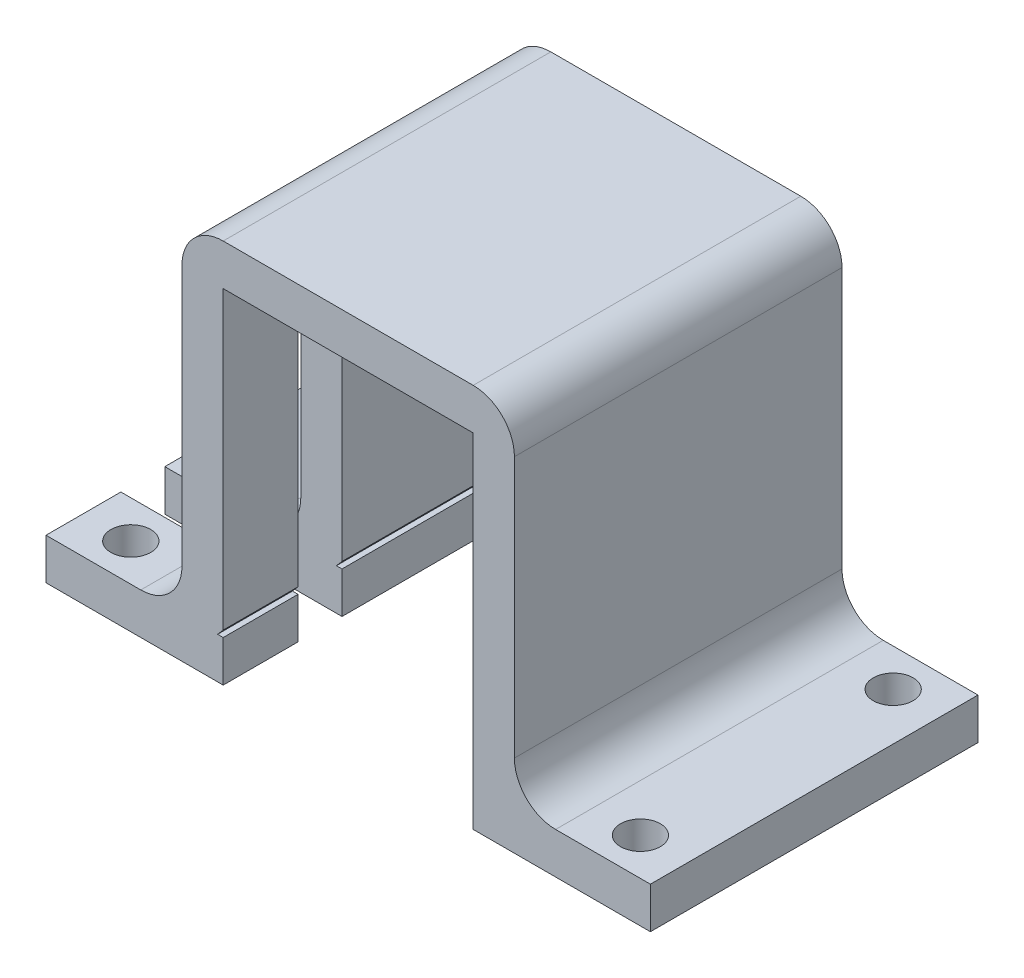
SolidWorks part; units mm, degrees
ref_plane "Front Plane" through (0, 0, 0) normal (0, 0, 1) x (1, 0, 0)
ref_plane "Top Plane" through (0, 0, 0) normal (0, 1, 0) x (1, 0, 0)
ref_plane "Right Plane" through (0, 0, 0) normal (1, 0, 0) x (0, 0, -1)
sketch "Sketch1" plane through (0, 0, 0) normal (0, 0, 1) x (1, 0, 0)
  line L1 (-9.1, 11) -> (9.1, 11)
  line L2 (-9.1, 11) -> (-9.1, -11)
  line L4 (9.1, 11) -> (9.1, -11)
  line L7 (-9.1, 14) -> (9.1, 14)
  line L8 (-12.1, 11) -> (-12.1, -8)
  line L9 (-12.1, -14) -> (-9.1, -14)
  line L10 (12.1, 11) -> (12.1, -8)
  line L12 (-9.1, -11) -> (-9.1, -14)
  line L13 (-22, -11) -> (-15.1, -11)
  line L14 (-22, -11) -> (-22, -14)
  line L15 (-22, -14) -> (-9.1, -14)
  line L16 (22, -11) -> (22, -14)
  line L17 (9.1, -11) -> (9.1, -14)
  line L18 (9.1, -14) -> (12.1, -14)
  line L19 (-9.5071, -11) -> (-9.1, -11)
  line L20 (-9.5071, -11) -> (-9.1, -10.5289) construction
  line L21 (15.1, -11) -> (22, -11)
  line L22 (9.1, -14) -> (22, -14)
  arc A0 (-9.1, 14) -> (-12.1, 11) centre (-9.1, 11) ccw
  arc A1 (9.1, 14) -> (12.1, 11) centre (9.1, 11) cw
  arc A2 (-12.1, -8) -> (-15.1, -11) centre (-15.1, -8) cw
  arc A3 (12.1, -8) -> (15.1, -11) centre (15.1, -8) ccw
  point P0 (0, 0)
  point P6 (0, 0)
  point P8 (12.1, -8)
  point P10 (0, 0)
  point P17 (0, -12.5)
  point P23 (0, 0)
  dimension "D5" = 3
  dimension "D9" = 3
  dimension "D1" = 22
  dimension "D2" = 18.2
  dimension "D3" = 3
  dimension "D4" = 3
  dimension "D6" = 3
  dimension "D7" = 44
  dimension "D8" = 14
  dimension "D10" = 3
  dimension "D11" = 9.9
  dimension "D12" = 9.9
  dimension "D13" = 9.1
  dimension "D14" = 9.1
extrude "Boss-Extrude1" add sketch "Sketch1" along normal blind 23.85 contours L19 L20 L2 L1 L4 L17 L18 L22 L16 L21 A3 L10 A1 L7 A0 L8 A2 L13 L14 L15 L9 L12
sketch "Sketch2" plane through (-12.1, 0, 0) normal (-1, 0, 0) x (0, 0, 1)
  line L0 (0, 0) -> (15.2, 0) construction
  line L1 (23.85, -14) -> (0, -14) construction
  line L2 (15.2, 6) -> (18.4, 6)
  line L3 (15.2, 6) -> (15.2, -14)
  line L4 (15.2, -14) -> (18.4, -14)
  line L5 (18.4, 6) -> (18.4, -14)
  point P9 (0, 0)
  point P10 (0, 0)
  point P11 (0, 0)
  dimension "D1" = 15.2
  dimension "D2" = 3.2
  dimension "D3" = 20
extrude "Cut-Extrude2" cut sketch "Sketch2" against normal blind 10 and the other way blind 12
sketch "Sketch4" plane through (0, -11, 0) normal (0, 1, 0) x (1, 0, 0)
  line L0 (22, -11.925) -> (-22, -11.925) construction
  line L1 (22, -23.85) -> (22, 0) construction
  line L2 (-22, -15.2) -> (-22, 0) construction
  line L3 (0, -23.85) -> (0, 0) construction
  line L4 (-9.1, -23.85) -> (9.1, -23.85) construction
  circle A0 centre (-18.55, -21.125) radius 1.45
  circle A1 centre (-18.55, -2.725) radius 1.45
  circle A2 centre (18.55, -21.125) radius 1.45
  circle A3 centre (18.55, -2.725) radius 1.45
  point P19 (0, 0)
  point P20 (0, 0)
  point P21 (0, 0)
  point P22 (0, 0)
  dimension "D1" = 2.9
  dimension "D2" = 3.45
  dimension "D3" = 9.2
extrude "Cut-Extrude3" cut sketch "Sketch4" against normal blind 10
